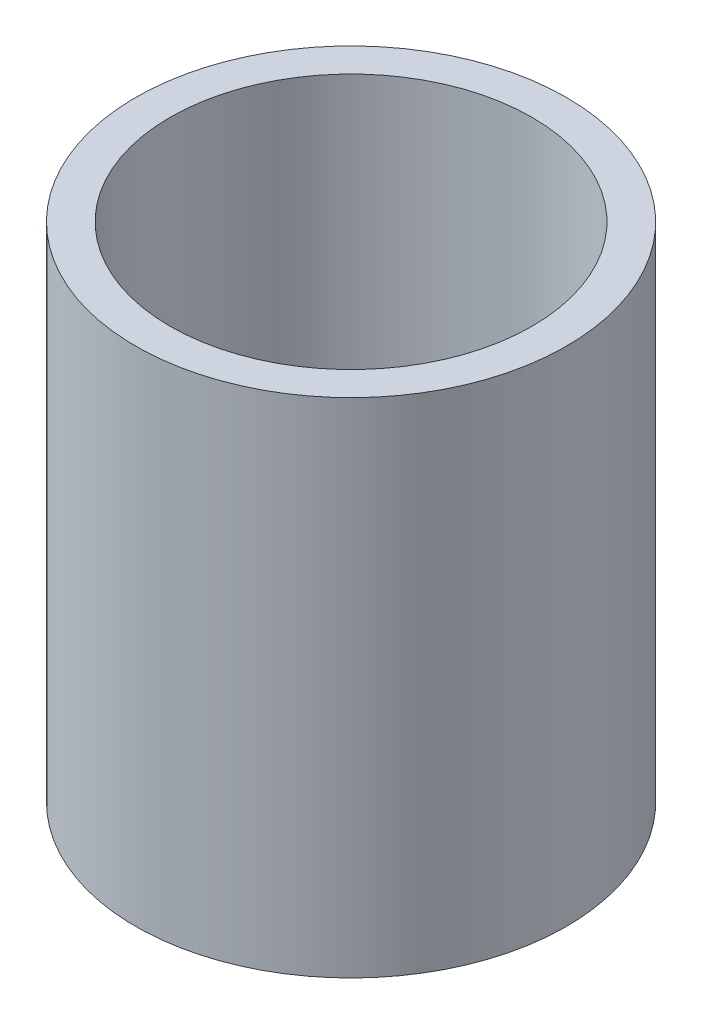
SolidWorks part; units mm, degrees
material "PVC 경질"
ref_plane "정면" through (0, 0, 0) normal (0, 0, 1) x (1, 0, 0)
ref_plane "윗면" through (0, 0, 0) normal (0, 1, 0) x (1, 0, 0)
ref_plane "우측면" through (0, 0, 0) normal (1, 0, 0) x (0, 0, -1)
other "질량 중심(COM)"
sketch "스케치1" plane through (0, 0, 0) normal (0, 1, 0) x (1, 0, 0)
  circle A0 centre (0, 0) radius 36
  circle A1 centre (0, 0) radius 30.25
  dimension "D1" = 72
  dimension "D2" = 60.5
extrude "보스-돌출1" add sketch "스케치1" along normal blind 84
